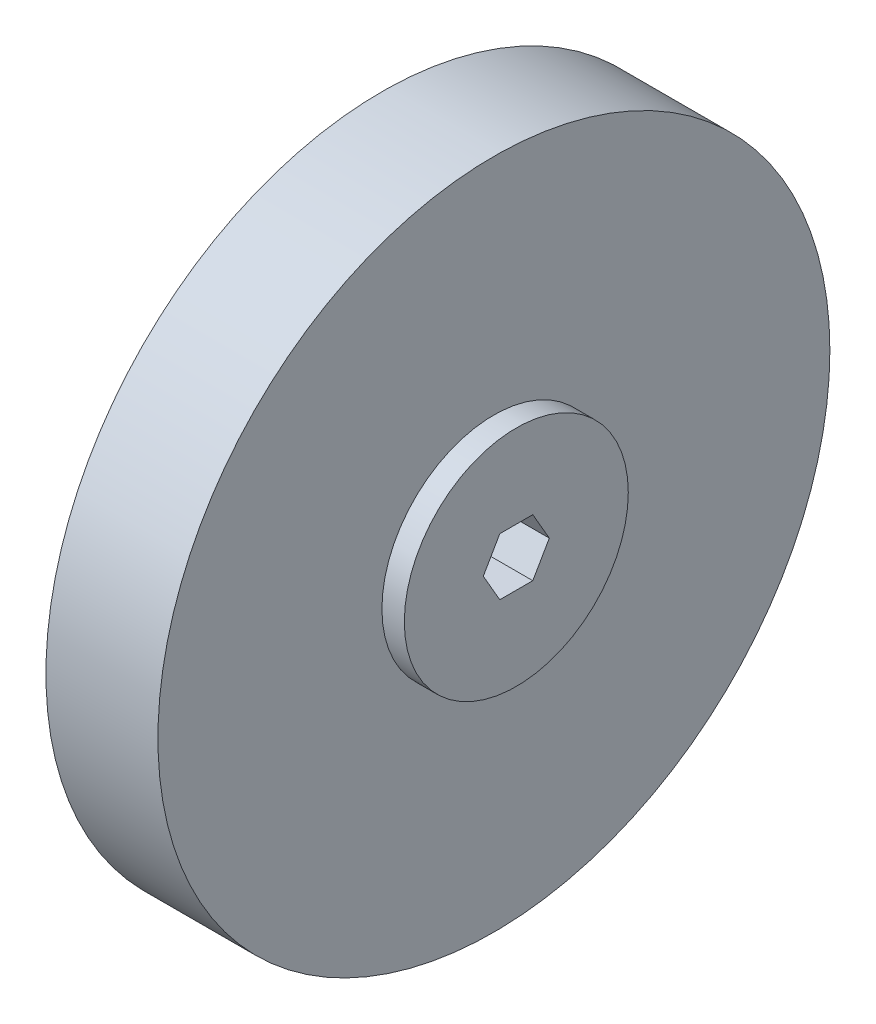
SolidWorks part; units mm, degrees
ref_plane "Front" through (0, 0, 0) normal (0, 0, 1) x (1, 0, 0)
ref_plane "Top" through (0, 0, 0) normal (0, 1, 0) x (1, 0, 0)
ref_plane "Right" through (0, 0, 0) normal (1, 0, 0) x (0, 0, -1)
sketch "草图3" plane through (0, 0, 0) normal (1, 0, 0) x (0, 0, -1)
  circle A0 centre (0, 0) radius 75
extrude "凸台-拉伸1" add sketch "草图3" along normal blind 25
sketch "草图4" plane through (25, 0, 0) normal (1, 0, 0) x (0, 0, -1)
  circle A0 centre (0, 0) radius 25
extrude "凸台-拉伸3" add sketch "草图4" along normal blind 5
sketch "草图6" plane through (0, 0, 0) normal (-1, 0, 0) x (0, 0, 1)
  circle A0 centre (0, 0) radius 25
extrude "凸台-拉伸4" add sketch "草图6" along normal blind 5
sketch "草图7" plane through (30, 0, 0) normal (1, 0, 0) x (0, 0, -1)
  line L1 (7.367, 0) -> (3.6835, 6.38)
  line L2 (3.6835, 6.38) -> (-3.6835, 6.38)
  line L3 (-3.6835, 6.38) -> (-7.367, 0)
  line L4 (-7.367, 0) -> (-3.6835, -6.38)
  line L5 (-3.6835, -6.38) -> (3.6835, -6.38)
  line L6 (3.6835, -6.38) -> (7.367, 0)
  circle A0 centre (0, 0) radius 6.38 construction
extrude "切除-拉伸3" cut sketch "草图7" against normal blind 40
